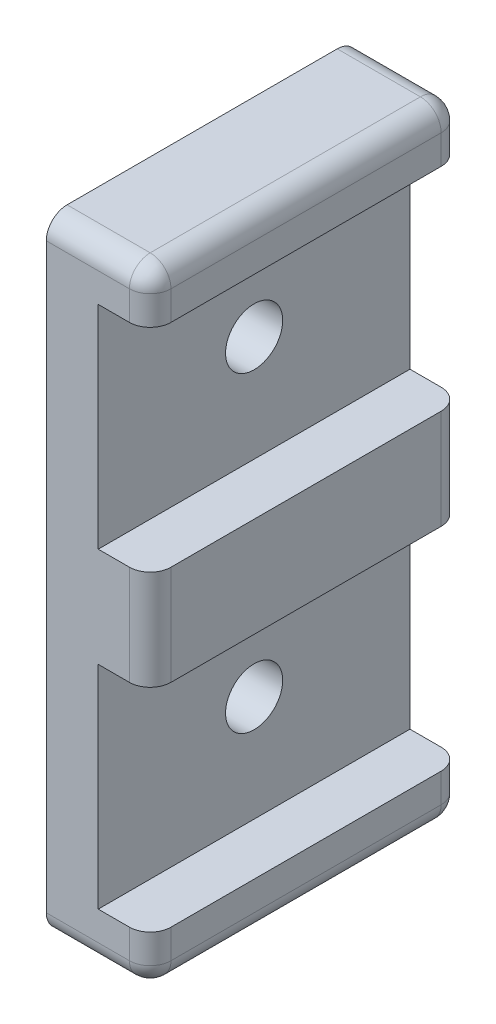
SolidWorks part; units mm, degrees
ref_plane "正面" through (0, 0, 0) normal (0, 0, 1) x (1, 0, 0)
ref_plane "平面" through (0, 0, 0) normal (0, 1, 0) x (1, 0, 0)
ref_plane "右側面" through (0, 0, 0) normal (1, 0, 0) x (0, 0, -1)
sketch "元ライン" plane through (0, 0, 0) normal (1, 0, 0) x (0, 0, -1)
  line L8 (0, 5) -> (0, -5) construction
  point P2 (0, 0)
  line B0 (-15, 25) -> (15, 25)
  line B1 (15, 25) -> (15, 5)
  line B2 (15, 5) -> (-15, 5)
  line B3 (-15, 5) -> (-15, 25)
  line B4 (-15, -5) -> (15, -5)
  line B5 (15, -5) -> (15, -25)
  line B6 (15, -25) -> (-15, -25)
  line B7 (-15, -25) -> (-15, -5)
  line B8 (-15, -19.4) -> (-15, -28)
  line B9 (-13, -30) -> (-4.4, -30)
  line B10 (-4, -29.6) -> (-4, -28.4)
  line B11 (-4.4, -28) -> (-8.25, -28)
  line B12 (-8.25, -28) -> (-8.25, -24.6642)
  line B13 (-8.25, -24.6642) -> (-4.5858, -21)
  line B14 (-4.5858, -21) -> (-2.425, -21)
  line B15 (-2.425, -21) -> (-1.2, -20.7619)
  line B16 (-1.2, -20.7619) -> (-0.9036, -20.933)
  line B17 (-0.4036, -20.933) -> (0, -20.7)
  line B18 (0, -20.7) -> (0.4036, -20.933)
  line B19 (0.9036, -20.933) -> (1.2, -20.7619)
  line B20 (1.2, -20.7619) -> (2.425, -21)
  line B21 (2.425, -21) -> (4.5858, -21)
  line B22 (4.5858, -21) -> (8.25, -24.6642)
  line B23 (8.25, -24.6642) -> (8.25, -28)
  line B24 (8.25, -28) -> (4.4, -28)
  line B25 (4, -28.4) -> (4, -29.6)
  line B26 (4.4, -30) -> (13, -30)
  line B27 (15, -28) -> (15, -19.4)
  line B28 (14.6, -19) -> (13.4, -19)
  line B29 (13, -19.4) -> (13, -23.25)
  line B30 (13, -23.25) -> (9.6642, -23.25)
  line B31 (9.6642, -23.25) -> (6, -19.5858)
  line B32 (6, -19.5858) -> (6, -17.425)
  line B33 (6, -17.425) -> (5.7619, -16.2)
  line B34 (5.7619, -16.2) -> (5.933, -15.9036)
  line B35 (5.933, -15.4036) -> (5.7, -15)
  line B36 (5.7, -15) -> (5.933, -14.5964)
  line B37 (5.933, -14.0964) -> (5.7619, -13.8)
  line B38 (5.7619, -13.8) -> (6, -12.575)
  line B39 (6, -12.575) -> (6, -10.4142)
  line B40 (6, -10.4142) -> (9.6642, -6.75)
  line B41 (9.6642, -6.75) -> (13, -6.75)
  line B42 (13, -6.75) -> (13, -10.6)
  line B43 (13.4, -11) -> (14.6, -11)
  line B44 (15, -10.6) -> (15, 10.6)
  line B45 (14.6, 11) -> (13.4, 11)
  line B46 (13, 10.6) -> (13, 6.75)
  line B47 (13, 6.75) -> (9.6642, 6.75)
  line B48 (9.6642, 6.75) -> (6, 10.4142)
  line B49 (6, 10.4142) -> (6, 12.575)
  line B50 (6, 12.575) -> (5.7619, 13.8)
  line B51 (5.7619, 13.8) -> (5.933, 14.0964)
  line B52 (5.933, 14.5964) -> (5.7, 15)
  line B53 (5.7, 15) -> (5.933, 15.4036)
  line B54 (5.933, 15.9036) -> (5.7619, 16.2)
  line B55 (5.7619, 16.2) -> (6, 17.425)
  line B56 (6, 17.425) -> (6, 19.5858)
  line B57 (6, 19.5858) -> (9.6642, 23.25)
  line B58 (9.6642, 23.25) -> (13, 23.25)
  line B59 (13, 23.25) -> (13, 19.4)
  line B60 (13.4, 19) -> (14.6, 19)
  line B61 (15, 19.4) -> (15, 28)
  line B62 (13, 30) -> (4.4, 30)
  line B63 (4, 29.6) -> (4, 28.4)
  line B64 (4.4, 28) -> (8.25, 28)
  line B65 (8.25, 28) -> (8.25, 24.6642)
  line B66 (8.25, 24.6642) -> (4.5858, 21)
  line B67 (4.5858, 21) -> (2.425, 21)
  line B68 (2.425, 21) -> (1.2, 20.7619)
  line B69 (1.2, 20.7619) -> (0.9036, 20.933)
  line B70 (0.4036, 20.933) -> (0, 20.7)
  line B71 (0, 20.7) -> (-0.4036, 20.933)
  line B72 (-0.9036, 20.933) -> (-1.2, 20.7619)
  line B73 (-1.2, 20.7619) -> (-2.425, 21)
  line B74 (-2.425, 21) -> (-4.5858, 21)
  line B75 (-4.5858, 21) -> (-8.25, 24.6642)
  line B76 (-8.25, 24.6642) -> (-8.25, 28)
  line B77 (-8.25, 28) -> (-4.4, 28)
  line B78 (-4, 28.4) -> (-4, 29.6)
  line B79 (-4.4, 30) -> (-13, 30)
  line B80 (-15, 28) -> (-15, 19.4)
  line B81 (-14.6, 19) -> (-13.4, 19)
  line B82 (-13, 19.4) -> (-13, 23.25)
  line B83 (-13, 23.25) -> (-9.6642, 23.25)
  line B84 (-9.6642, 23.25) -> (-6, 19.5858)
  line B85 (-6, 19.5858) -> (-6, 17.425)
  line B86 (-6, 17.425) -> (-5.7619, 16.2)
  line B87 (-5.7619, 16.2) -> (-5.933, 15.9036)
  line B88 (-5.933, 15.4036) -> (-5.7, 15)
  line B89 (-5.7, 15) -> (-5.933, 14.5964)
  line B90 (-5.933, 14.0964) -> (-5.7619, 13.8)
  line B91 (-5.7619, 13.8) -> (-6, 12.575)
  line B92 (-6, 12.575) -> (-6, 10.4142)
  line B93 (-6, 10.4142) -> (-9.6642, 6.75)
  line B94 (-9.6642, 6.75) -> (-13, 6.75)
  line B95 (-13, 6.75) -> (-13, 10.6)
  line B96 (-13.4, 11) -> (-14.6, 11)
  line B97 (-15, 10.6) -> (-15, -10.6)
  line B98 (-14.6, -11) -> (-13.4, -11)
  line B99 (-13, -10.6) -> (-13, -6.75)
  line B100 (-13, -6.75) -> (-9.6642, -6.75)
  line B101 (-9.6642, -6.75) -> (-6, -10.4142)
  line B102 (-6, -10.4142) -> (-6, -12.575)
  line B103 (-6, -12.575) -> (-5.7619, -13.8)
  line B104 (-5.7619, -13.8) -> (-5.933, -14.0964)
  line B105 (-5.933, -14.5964) -> (-5.7, -15)
  line B106 (-5.7, -15) -> (-5.933, -15.4036)
  line B107 (-5.933, -15.9036) -> (-5.7619, -16.2)
  line B108 (-5.7619, -16.2) -> (-6, -17.425)
  line B109 (-6, -17.425) -> (-6, -19.5858)
  line B110 (-6, -19.5858) -> (-9.6642, -23.25)
  line B111 (-9.6642, -23.25) -> (-13, -23.25)
  line B112 (-13, -23.25) -> (-13, -19.4)
  line B113 (-13.4, -19) -> (-14.6, -19)
  arc B114 (-14.6, -19) -> (-15, -19.4) centre (-14.6, -19.4) ccw
  arc B115 (-15, -28) -> (-13, -30) centre (-13, -28) ccw
  arc B116 (-4.4, -30) -> (-4, -29.6) centre (-4.4, -29.6) ccw
  arc B117 (-4, -28.4) -> (-4.4, -28) centre (-4.4, -28.4) ccw
  arc B118 (-0.9036, -20.933) -> (-0.4036, -20.933) centre (-0.6536, -20.5) ccw
  arc B119 (0.4036, -20.933) -> (0.9036, -20.933) centre (0.6536, -20.5) ccw
  arc B120 (4.4, -28) -> (4, -28.4) centre (4.4, -28.4) ccw
  arc B121 (4, -29.6) -> (4.4, -30) centre (4.4, -29.6) ccw
  arc B122 (13, -30) -> (15, -28) centre (13, -28) ccw
  arc B123 (15, -19.4) -> (14.6, -19) centre (14.6, -19.4) ccw
  arc B124 (13.4, -19) -> (13, -19.4) centre (13.4, -19.4) ccw
  arc B125 (5.933, -15.9036) -> (5.933, -15.4036) centre (5.5, -15.6536) ccw
  arc B126 (5.933, -14.5964) -> (5.933, -14.0964) centre (5.5, -14.3464) ccw
  arc B127 (13, -10.6) -> (13.4, -11) centre (13.4, -10.6) ccw
  arc B128 (14.6, -11) -> (15, -10.6) centre (14.6, -10.6) ccw
  arc B129 (15, 10.6) -> (14.6, 11) centre (14.6, 10.6) ccw
  arc B130 (13.4, 11) -> (13, 10.6) centre (13.4, 10.6) ccw
  arc B131 (5.933, 14.0964) -> (5.933, 14.5964) centre (5.5, 14.3464) ccw
  arc B132 (5.933, 15.4036) -> (5.933, 15.9036) centre (5.5, 15.6536) ccw
  arc B133 (13, 19.4) -> (13.4, 19) centre (13.4, 19.4) ccw
  arc B134 (14.6, 19) -> (15, 19.4) centre (14.6, 19.4) ccw
  arc B135 (15, 28) -> (13, 30) centre (13, 28) ccw
  arc B136 (4.4, 30) -> (4, 29.6) centre (4.4, 29.6) ccw
  arc B137 (4, 28.4) -> (4.4, 28) centre (4.4, 28.4) ccw
  arc B138 (0.9036, 20.933) -> (0.4036, 20.933) centre (0.6536, 20.5) ccw
  arc B139 (-0.4036, 20.933) -> (-0.9036, 20.933) centre (-0.6536, 20.5) ccw
  arc B140 (-4.4, 28) -> (-4, 28.4) centre (-4.4, 28.4) ccw
  arc B141 (-4, 29.6) -> (-4.4, 30) centre (-4.4, 29.6) ccw
  arc B142 (-13, 30) -> (-15, 28) centre (-13, 28) ccw
  arc B143 (-15, 19.4) -> (-14.6, 19) centre (-14.6, 19.4) ccw
  arc B144 (-13.4, 19) -> (-13, 19.4) centre (-13.4, 19.4) ccw
  arc B145 (-5.933, 15.9036) -> (-5.933, 15.4036) centre (-5.5, 15.6536) ccw
  arc B146 (-5.933, 14.5964) -> (-5.933, 14.0964) centre (-5.5, 14.3464) ccw
  arc B147 (-13, 10.6) -> (-13.4, 11) centre (-13.4, 10.6) ccw
  arc B148 (-14.6, 11) -> (-15, 10.6) centre (-14.6, 10.6) ccw
  arc B149 (-15, -10.6) -> (-14.6, -11) centre (-14.6, -10.6) ccw
  arc B150 (-13.4, -11) -> (-13, -10.6) centre (-13.4, -10.6) ccw
  arc B151 (-5.933, -14.0964) -> (-5.933, -14.5964) centre (-5.5, -14.3464) ccw
  arc B152 (-5.933, -15.4036) -> (-5.933, -15.9036) centre (-5.5, -15.6536) ccw
  arc B153 (-13, -19.4) -> (-13.4, -19) centre (-13.4, -19.4) ccw
sketch_block_instance "ﾌﾞﾛｯｸ1-1"
sketch_block "ﾌﾞﾛｯｸ1"
sketch "ｽｹｯﾁ2" plane through (0, 0, 0) normal (1, 0, 0) x (0, 0, -1)
  line L0 (-15, 28) -> (-15, 19.4) construction
  line L1 (-4.4, 30) -> (-13, 30) construction
  line L2 (-15, 28) -> (-15, -28)
  line L3 (13, 30) -> (-13, 30)
  line L4 (15, -28) -> (15, -19.4) construction
  line L5 (-13, -30) -> (-4.4, -30) construction
  line L6 (15, -28) -> (15, 28)
  line L7 (-13, -30) -> (13, -30)
  line L8 (0, 30) -> (0, -30) construction
  line L9 (-15, 15) -> (15, 15) construction
  line L10 (-15, 0) -> (15, 0) construction
  arc A0 (-15, -28) -> (-13, -30) centre (-13, -28) ccw construction
  arc A1 (13, -30) -> (15, -28) centre (13, -28) ccw construction
  arc A2 (15, 28) -> (13, 30) centre (13, 28) ccw construction
  arc A3 (-13, 30) -> (-15, 28) centre (-13, 28) ccw construction
  arc A4 (-15, -28) -> (-13, -30) centre (-13, -28) ccw
  arc A5 (13, -30) -> (15, -28) centre (13, -28) ccw
  arc A6 (15, 28) -> (13, 30) centre (13, 28) ccw
  arc A7 (-13, 30) -> (-15, 28) centre (-13, 28) ccw
  circle A8 centre (0, 15) radius 2.75
  circle A9 centre (0, -15) radius 2.75
  dimension "D2" = 5.5
  dimension "D1" = 15
extrude "ﾎﾞｽ - 押し出し1" add sketch "ｽｹｯﾁ2" against normal blind 5
sketch "ｽｹｯﾁ4" plane through (0, 0, 0) normal (1, 0, 0) x (0, 0, -1)
  line L0 (15, -25) -> (-15, -25) construction
  line L1 (-15, -5) -> (15, -5) construction
  line L2 (15, 5) -> (-15, 5) construction
  line L3 (-15, 25) -> (15, 25) construction
  line L4 (15, -25) -> (-15, -25) construction
  line L5 (-15, -5) -> (15, -5) construction
  line L6 (15, 5) -> (-15, 5) construction
  line L7 (-15, 25) -> (15, 25) construction
  line L8 (-15, 25.2) -> (15, 25.2)
  line L9 (-15, -4.8) -> (15, -4.8)
  line L10 (15, 4.8) -> (-15, 4.8)
  line L11 (15, -25.2) -> (-15, -25.2)
  line L12 (-15, 25.2) -> (-15, 4.8)
  line L13 (15, 25.2) -> (15, 4.8)
  line L14 (-15, -4.8) -> (-15, -25.2)
  line L15 (15, -4.8) -> (15, -25.2)
  arc M7 (-15, -28) -> (-13, -30) centre (-13, -28) ccw
  line M8 (-13, -30) -> (13, -30)
  arc M9 (13, -30) -> (15, -28) centre (13, -28) ccw
  line M10 (15, -28) -> (15, 28)
  arc M11 (15, 28) -> (13, 30) centre (13, 28) ccw
  line M12 (13, 30) -> (-13, 30)
  arc M13 (-13, 30) -> (-15, 28) centre (-13, 28) ccw
  line M14 (-15, 28) -> (-15, -28)
  dimension "D1" = 0.2
  dimension "D2" = 0.2
extrude "ﾎﾞｽ - 押し出し2" add sketch "ｽｹｯﾁ4" along normal blind 5 contours L8 M14 M10 M11 M12 M13 | L10 L9 M10 M14 | L11 M10 M14 M7 M8 M9
fillet "ﾌｨﾚｯﾄ1" radius 2 12 edges at (5, -26.6, 15) (5, -29.4142, 14.4142) (5, -30, 0) (5, -29.4142, -14.4142) (5, 26.6, -15) (5, 29.4142, -14.4142) (5, 30, 0) (5, 29.4142, 14.4142) (5, -26.6, -15) (5, 0, -15) (5, 0, 15) (5, 26.6, 15)
